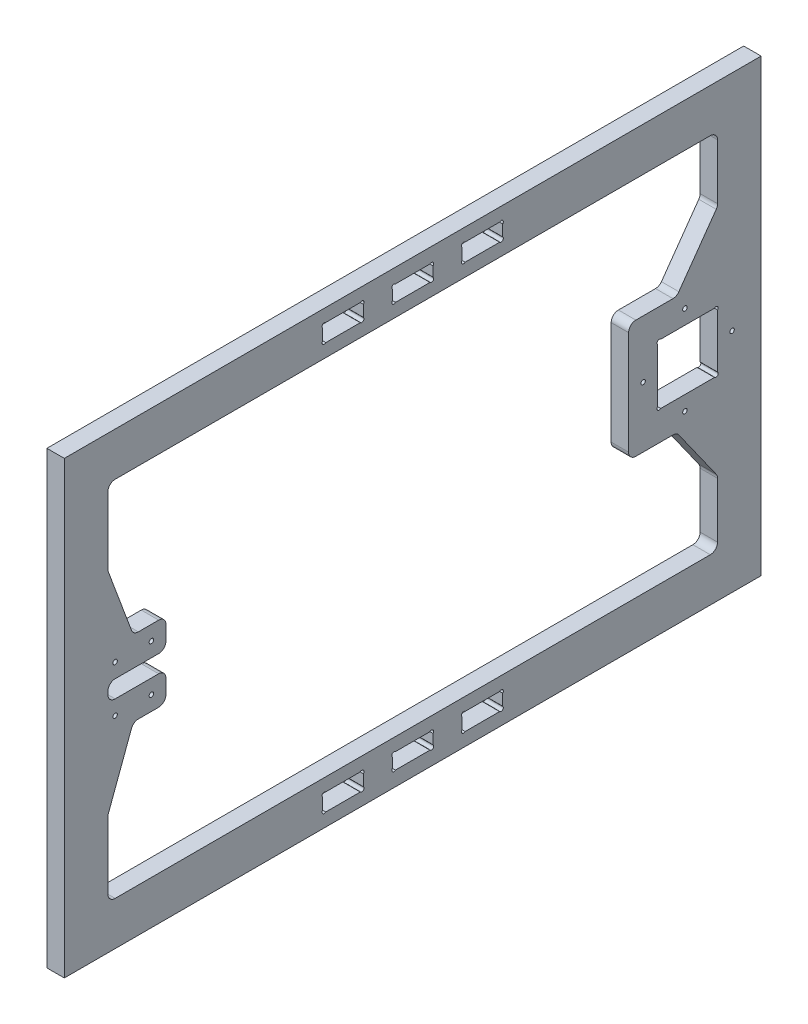
SolidWorks part; units mm, degrees
ref_plane "Alzado" through (0, 0, 0) normal (0, 0, 1) x (1, 0, 0)
ref_plane "Planta" through (0, 0, 0) normal (0, 1, 0) x (1, 0, 0)
ref_plane "Vista lateral" through (0, 0, 0) normal (1, 0, 0) x (0, 0, -1)
sketch "Croquis1" plane through (0, 0, 0) normal (1, 0, 0) x (0, 0, -1)
  line L0 (30, -30) -> (450, -30)
  line L1 (0, 0) -> (480, 0)
  line L2 (0, 0) -> (0, -310)
  line L3 (0, -310) -> (480, -310)
  line L4 (480, 0) -> (480, -310)
  line L5 (70, -129) -> (70, -149)
  line L6 (30, -280) -> (450, -280)
  line L7 (30, -30) -> (30, -129)
  line L8 (302, -301) -> (302, -289)
  line L9 (274, -289) -> (302, -289)
  line L10 (254, -300) -> (254, -289)
  line L11 (226, -289) -> (254, -289)
  line L12 (226, -300) -> (226, -289)
  line L13 (226, -300) -> (254, -300)
  line L14 (274, -301) -> (274, -289)
  line L15 (274, -301) -> (302, -301)
  line L16 (206, -301) -> (206, -289)
  line L17 (178, -289) -> (206, -289)
  line L18 (178, -301) -> (178, -289)
  line L19 (178, -301) -> (206, -301)
  line L20 (450, -114.35) -> (388.7, -114.35)
  line L21 (178, -9) -> (206, -9)
  line L22 (178, -9) -> (178, -21)
  line L23 (178, -21) -> (206, -21)
  line L24 (206, -9) -> (206, -21)
  line L25 (274, -9) -> (302, -9)
  line L26 (274, -9) -> (274, -21)
  line L27 (226, -10) -> (254, -10)
  line L28 (226, -10) -> (226, -21)
  line L29 (226, -21) -> (254, -21)
  line L30 (254, -10) -> (254, -21)
  line L31 (274, -21) -> (302, -21)
  line L32 (302, -9) -> (302, -21)
  line L33 (450, -30) -> (450, -114.35)
  line L34 (388.7, -114.35) -> (388.7, -195.65)
  line L35 (450, -195.65) -> (388.7, -195.65)
  line L36 (70, -161) -> (30, -161)
  line L37 (450, -30) -> (450, -280) construction
  line L38 (408.7, -134.35) -> (450, -134.35)
  line L39 (408.7, -134.35) -> (408.7, -175.65)
  line L40 (450, -195.65) -> (450, -280)
  line L41 (408.7, -175.65) -> (450, -175.65)
  line L42 (450, -134.35) -> (450, -175.65)
  line L43 (30, -181) -> (70, -181)
  line L44 (30, -129) -> (70, -129)
  line L46 (70, -149) -> (30, -149)
  line L47 (70, -161) -> (70, -181)
  line L48 (408.7, -155) -> (398.7, -155) construction
  line L49 (30, -149) -> (30, -161)
  line L50 (30, -30) -> (30, -280) construction
  line L51 (30, -181) -> (30, -280)
  line L52 (30, -155) -> (129.1317, -155) construction
  dimension "D1" = 30
  dimension "D3" = 310
  dimension "D4" = 40
  dimension "D5" = 480
  dimension "D6" = 41.3
  dimension "D7" = 178
  dimension "D8" = 28
  dimension "D9" = 20
  dimension "D10" = 9
  dimension "D11" = 9
  dimension "D12" = 10
  dimension "D13" = 9
  dimension "D14" = 20
  dimension "D15" = 20
  dimension "D16" = 9
  dimension "D17" = 9
  dimension "D18" = 28
  dimension "D19" = 28
  dimension "D20" = 20
  dimension "D21" = 30
  dimension "D22" = 20
  dimension "D23" = 40
  dimension "D24" = 20
  dimension "D25" = 20
  dimension "D26" = 12
  dimension "D27" = 41.3
  dimension "D28" = 125
  dimension "D29" = 125
extrude "Saliente-Extruir1" add sketch "Croquis1" along normal blind 12 contours L1 L4 L3 L2
sketch "Sketch1" plane through (12, 0, 0) normal (1, 0, 0) x (0, 0, -1)
  line L0 (178, -9) -> (179.0607, -10.0607) construction
  line L1 (206, -9) -> (204.9393, -10.0607) construction
  line L2 (206, -9) -> (178, -9) construction
  line L3 (226, -10) -> (227.0607, -11.0607) construction
  line L4 (226, -21) -> (227.0607, -19.9393) construction
  line L5 (254, -21) -> (252.9393, -19.9393) construction
  line L6 (254, -10) -> (252.9393, -11.0607) construction
  line L7 (274, -9) -> (275.0607, -10.0607) construction
  line L8 (274, -21) -> (275.0607, -19.9393) construction
  line L9 (302, -9) -> (300.9393, -10.0607) construction
  line L10 (302, -21) -> (300.9393, -19.9393) construction
  line L11 (30, -155) -> (112.501, -155) construction
  line L12 (178, -21) -> (179.0607, -19.9393) construction
  line L13 (206, -21) -> (204.9393, -19.9393) construction
  line L14 (178, -21) -> (206, -21) construction
  line L15 (206, -289) -> (204.9393, -290.0607) construction
  line L16 (178, -289) -> (179.0607, -290.0607) construction
  line L17 (302, -289) -> (300.9393, -290.0607) construction
  line L18 (302, -301) -> (300.9393, -299.9393) construction
  line L19 (274, -289) -> (275.0607, -290.0607) construction
  line L20 (274, -301) -> (275.0607, -299.9393) construction
  line L21 (254, -300) -> (252.9393, -298.9393) construction
  line L22 (254, -289) -> (252.9393, -290.0607) construction
  line L25 (226, -289) -> (227.0607, -290.0607) construction
  line L26 (226, -300) -> (227.0607, -298.9393) construction
  line L27 (408.7, -134.35) -> (409.7607, -135.4107) construction
  line L28 (408.7, -175.65) -> (409.7607, -174.5893) construction
  line L29 (450, -134.35) -> (448.9393, -135.4107) construction
  line L30 (450, -175.65) -> (448.9393, -174.5893) construction
  line L31 (254, -10) -> (226, -10) construction
  line L32 (254, -21) -> (254, -10) construction
  line L33 (226, -21) -> (254, -21) construction
  line L34 (302, -9) -> (274, -9) construction
  line L35 (274, -9) -> (274, -21) construction
  line L36 (302, -21) -> (302, -9) construction
  line L37 (450, -175.65) -> (450, -134.35) construction
  line L38 (450, -134.35) -> (408.7, -134.35) construction
  line L39 (408.7, -134.35) -> (408.7, -175.65) construction
  line L40 (206, -301) -> (204.9393, -299.9393) construction
  line L41 (178, -301) -> (179.0607, -299.9393) construction
  line L50 (30, -149) -> (30, -161) construction
  circle A0 centre (204.9393, -10.0607) radius 1.5
  circle A1 centre (179.0607, -10.0607) radius 1.5
  circle A2 centre (227.0607, -11.0607) radius 1.5
  circle A3 centre (227.0607, -19.9393) radius 1.5
  circle A4 centre (252.9393, -11.0607) radius 1.5
  circle A5 centre (252.9393, -19.9393) radius 1.5
  circle A6 centre (275.0607, -10.0607) radius 1.5
  circle A7 centre (275.0607, -19.9393) radius 1.5
  circle A8 centre (300.9393, -19.9393) radius 1.5
  circle A9 centre (300.9393, -10.0607) radius 1.5
  circle A10 centre (409.7607, -135.4107) radius 1.5
  circle A11 centre (448.9393, -135.4107) radius 1.5
  circle A12 centre (448.9393, -174.5893) radius 1.5
  circle A13 centre (409.7607, -174.5893) radius 1.5
  circle A14 centre (179.0607, -19.9393) radius 1.5
  circle A15 centre (204.9393, -19.9393) radius 1.5
  circle A16 centre (204.9393, -290.0607) radius 1.5
  circle A17 centre (179.0607, -290.0607) radius 1.5
  circle A18 centre (300.9393, -299.9393) radius 1.5
  circle A19 centre (300.9393, -290.0607) radius 1.5
  circle A20 centre (275.0607, -290.0607) radius 1.5
  circle A21 centre (275.0607, -299.9393) radius 1.5
  circle A22 centre (252.9393, -290.0607) radius 1.5
  circle A23 centre (252.9393, -298.9393) radius 1.5
  circle A24 centre (227.0607, -290.0607) radius 1.5
  circle A25 centre (227.0607, -298.9393) radius 1.5
  circle A28 centre (179.0607, -299.9393) radius 1.5
  circle A29 centre (204.9393, -299.9393) radius 1.5
  dimension "D1" = 45
  dimension "D2" = 45
  dimension "D3" = 1.5
  dimension "D4" = 1.5
  dimension "D5" = 45
  dimension "D6" = 45
  dimension "D7" = 45
  dimension "D8" = 45
  dimension "D9" = 45
  dimension "D10" = 45
  dimension "D11" = 45
  dimension "D12" = 1.5
  dimension "D13" = 45
  dimension "D14" = 45
  dimension "D15" = 45
  dimension "D16" = 45
  dimension "D17" = 45
  dimension "D18" = 1.5
  dimension "D19" = 45
  dimension "D20" = 45
  dimension "D21" = 1.5
  dimension "D34" = 1.5
  dimension "D35" = 1.5
  dimension "D36" = 1.5
  dimension "D37" = 1.5
  dimension "D38" = 1.5
  dimension "D39" = 1.5
  dimension "D40" = 1.5
  dimension "D41" = 1.5
  dimension "D42" = 1.5
  dimension "D43" = 1.5
  dimension "D44" = 1.5
extrude "Cut-Extrude1" cut sketch "Sketch1" against normal through all
sketch "Sketch2" plane through (12, 0, 0) normal (1, 0, 0) x (0, 0, -1)
  line L0 (70, -161) -> (70, -181) construction
  line L1 (30, -181) -> (30, -280) construction
  line L2 (70, -181) -> (30, -181) construction
  line L3 (30, -155) -> (50.4966, -155) construction
  line L4 (30, -149) -> (30, -161) construction
  circle A0 centre (60, -171) radius 1.55
  circle A1 centre (35, -171) radius 1.55
  circle A2 centre (35, -139) radius 1.55
  circle A3 centre (60, -139) radius 1.55
  dimension "D1" = 10
  dimension "D2" = 5
  dimension "D3" = 3.1
  dimension "D4" = 3.1
  dimension "D5" = 10
  dimension "D6" = 10
extrude "Cut-Extrude2" cut sketch "Sketch2" against normal up to surface (12 mm away) up to face at (0, -15.5, -240)
fillet "Fillet1" radius 5 12 edges at (6, -195.65, -388.7) (6, -114.35, -388.7) (6, -181, -70) (6, -161, -70) (6, -129, -70) (6, -149, -70) (6, -161, -30) (6, -149, -30) (6, -280, -450) (6, -30, -450) (6, -280, -30) (6, -30, -30)
sketch "Sketch3" plane through (12, 0, 0) normal (1, 0, 0) x (0, 0, -1)
  line L0 (393.7, -114.35) -> (450, -114.35) construction
  line L1 (450, -195.65) -> (393.7, -195.65) construction
  line L3 (408.7, -136.4713) -> (408.7, -173.5287) construction
  line L4 (450, -173.5287) -> (450, -136.4713) construction
  circle A0 centre (427.5246, -185.65) radius 1.55
  circle A1 centre (460, -153.9127) radius 1.55
  circle A2 centre (427.5246, -124.35) radius 1.55
  circle A3 centre (398.7, -153.9127) radius 1.55
  dimension "D1" = 10
  dimension "D2" = 10
  dimension "D3" = 3.1
  dimension "D4" = 3.1
  dimension "D5" = 10
  dimension "D6" = 3.1
  dimension "D7" = 3.1
  dimension "D8" = 10
extrude "Cut-Extrude3" cut sketch "Sketch3" against normal up to surface (12 mm away) up to face at (0, -139, -61.55)
sketch "Sketch4" plane through (12, 0, 0) normal (1, 0, 0) x (0, 0, -1)
  line L0 (421.85, -114.35) -> (450, -74.675)
  line L3 (421.85, -195.65) -> (450, -235.325)
  line L4 (450, -195.65) -> (393.7, -195.65) construction
  line L5 (450, -275) -> (450, -195.65) construction
  line L6 (393.7, -114.35) -> (450, -114.35) construction
  line L7 (450, -114.35) -> (450, -35) construction
  line L8 (450, -74.675) -> (450, -114.35)
  line L9 (450, -114.35) -> (421.85, -114.35)
  line L10 (450, -235.325) -> (450, -195.65)
  line L11 (450, -195.65) -> (421.85, -195.65)
  line L12 (47.5, -129) -> (30, -82)
  line L13 (30, -129) -> (65, -129) construction
  line L14 (30, -35) -> (30, -129) construction
  line L15 (30, -82) -> (30, -129)
  line L16 (30, -129) -> (47.5, -129)
  line L17 (47.5, -181) -> (30, -228)
  line L18 (65, -181) -> (30, -181) construction
  line L19 (30, -181) -> (30, -275) construction
  line L20 (30, -228) -> (30, -181)
  line L21 (30, -181) -> (47.5, -181)
extrude "Boss-Extrude1" add sketch "Sketch4" against normal blind 12
fillet "Fillet2" radius 5 8 edges at (6, -235.325, -450) (6, -195.65, -421.85) (6, -114.35, -421.85) (6, -74.675, -450) (6, -181, -47.5) (6, -228, -30) (6, -129, -47.5) (6, -82, -30)
